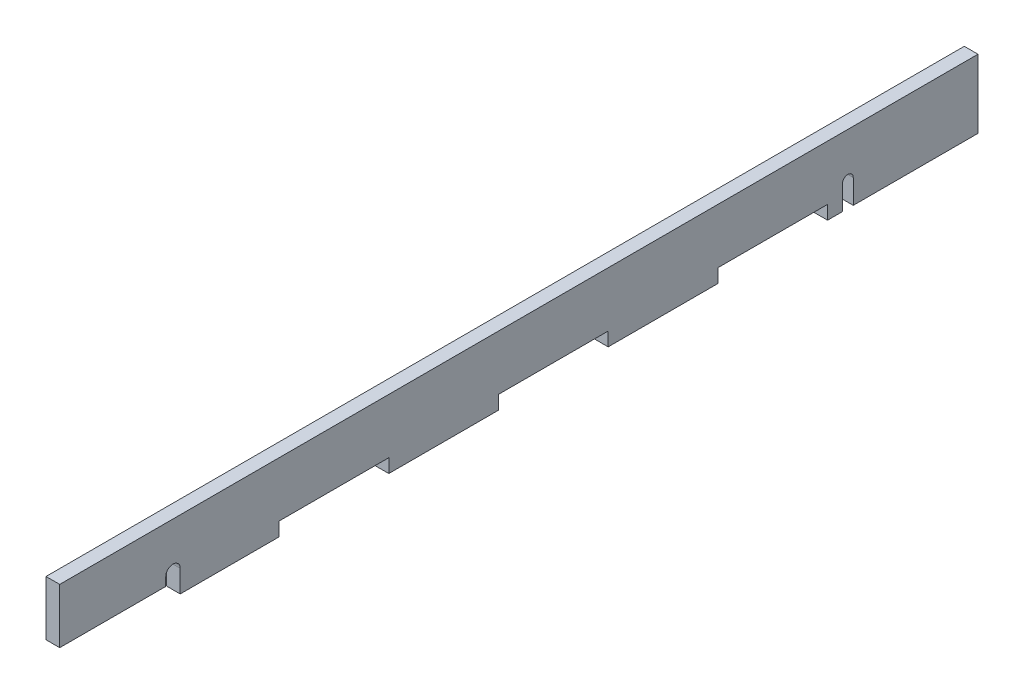
SolidWorks part; units mm, degrees
ref_plane "Front Plane" through (0, 0, 0) normal (0, 0, 1) x (1, 0, 0)
ref_plane "Top Plane" through (0, 0, 0) normal (0, 1, 0) x (1, 0, 0)
ref_plane "Right Plane" through (0, 0, 0) normal (1, 0, 0) x (0, 0, -1)
sketch "Sketch2" plane through (0, 0, 0) normal (1, 0, 0) x (0, 0, -1)
  line L30 (48.3194, 0) -> (99.1194, 0)
  line L31 (-2.4806, 6.35) -> (-2.4806, 31.75)
  line L32 (-2.4806, 31.75) -> (422.7895, 31.75)
  line L33 (422.7895, 0) -> (422.7895, 31.75)
  line L34 (353.1194, 6.35) -> (353.1194, 0) construction
  line L35 (302.3194, 6.35) -> (353.1194, 6.35) construction
  line L36 (302.3194, 6.35) -> (302.3194, 0) construction
  line L37 (251.5194, 6.35) -> (251.5194, 0) construction
  line L38 (200.7194, 6.35) -> (251.5194, 6.35) construction
  line L39 (200.7194, 6.35) -> (200.7194, 0) construction
  line L40 (149.9194, 6.35) -> (149.9194, 0) construction
  line L41 (99.1194, 6.35) -> (149.9194, 6.35) construction
  line L42 (99.1194, 6.35) -> (99.1194, 0) construction
  line L43 (48.3194, 6.35) -> (48.3194, 0) construction
  line L44 (-2.4806, 6.35) -> (48.3194, 6.35) construction
  line L45 (422.7895, 31.75) -> (422.7895, 35.3357) construction
  line L46 (353.1194, 6.35) -> (353.1194, 0)
  line L47 (302.3194, 6.35) -> (353.1194, 6.35)
  line L48 (302.3194, 6.35) -> (302.3194, 0)
  line L49 (251.5194, 6.35) -> (251.5194, 0)
  line L50 (200.7194, 6.35) -> (251.5194, 6.35)
  line L51 (200.7194, 6.35) -> (200.7194, 0)
  line L52 (149.9194, 6.35) -> (149.9194, 0)
  line L53 (99.1194, 6.35) -> (149.9194, 6.35)
  line L54 (99.1194, 6.35) -> (99.1194, 0)
  line L55 (48.3194, 6.35) -> (48.3194, 0)
  line L56 (-2.4806, 6.35) -> (48.3194, 6.35)
  line L57 (353.1194, 0) -> (422.7895, 0)
  line L58 (251.5194, 0) -> (302.3194, 0)
  line L59 (149.9194, 0) -> (200.7194, 0)
extrude "Boss-Extrude1" add sketch "Sketch2" along normal blind 6.35
sketch "Sketch3" plane through (6.35, 0, 0) normal (1, 0, 0) x (0, 0, -1)
  line L0 (353.1194, 6.35) -> (422.7895, 6.35) construction
  line L1 (422.7895, 0) -> (422.7895, 31.75) construction
  line L2 (362.5194, 8.66) -> (362.5194, 6.35) construction
  line L3 (-2.4806, 31.75) -> (-2.4806, 6.35) construction
  line L5 (365.0194, 11.16) -> (365.0194, -0.0346)
  line L6 (360.0194, 11.16) -> (360.0194, -0.0346)
  line L7 (365.0194, -0.0346) -> (360.0194, -0.0346)
  arc A0 (365.0194, 11.16) -> (360.0194, 11.16) centre (362.5194, 11.16) ccw
  dimension "D1" = 5
  dimension "D2" = 2.31
  dimension "D3" = 365
extrude "Cut-Extrude1" cut sketch "Sketch3" against normal up to next
sketch "Sketch4" plane through (6.35, 0, 0) normal (1, 0, 0) x (0, 0, -1)
  line L1 (53.3194, 10.31) -> (53.3194, 0)
  line L2 (48.3194, 6.35) -> (48.3194, 0)
  line L3 (53.3194, 0) -> (48.3194, 0)
  line L4 (48.3194, 0) -> (99.1194, 0) construction
  line L6 (-2.4806, 6.35) -> (48.3194, 6.35) construction
  line L7 (48.3194, 6.35) -> (48.3194, 0) construction
  line L9 (48.3194, 6.35) -> (46.6194, 6.35)
  line L10 (46.6194, 10.31) -> (46.6194, 6.35)
  arc A1 (53.3194, 10.31) -> (46.6194, 10.31) centre (49.9694, 10.31) ccw
  point P1 (49.9694, 13.66)
  point P2 (46.3194, 11.4202)
  point P4 (46.3194, 10.16)
  point P5 (42.0778, 6.35)
  point P9 (0, 0)
  point P10 (0, 0)
  dimension "D1" = 7.31
  dimension "D2" = 1.7
  dimension "D4" = 5
extrude "Cut-Extrude2" cut sketch "Sketch4" against normal through all
